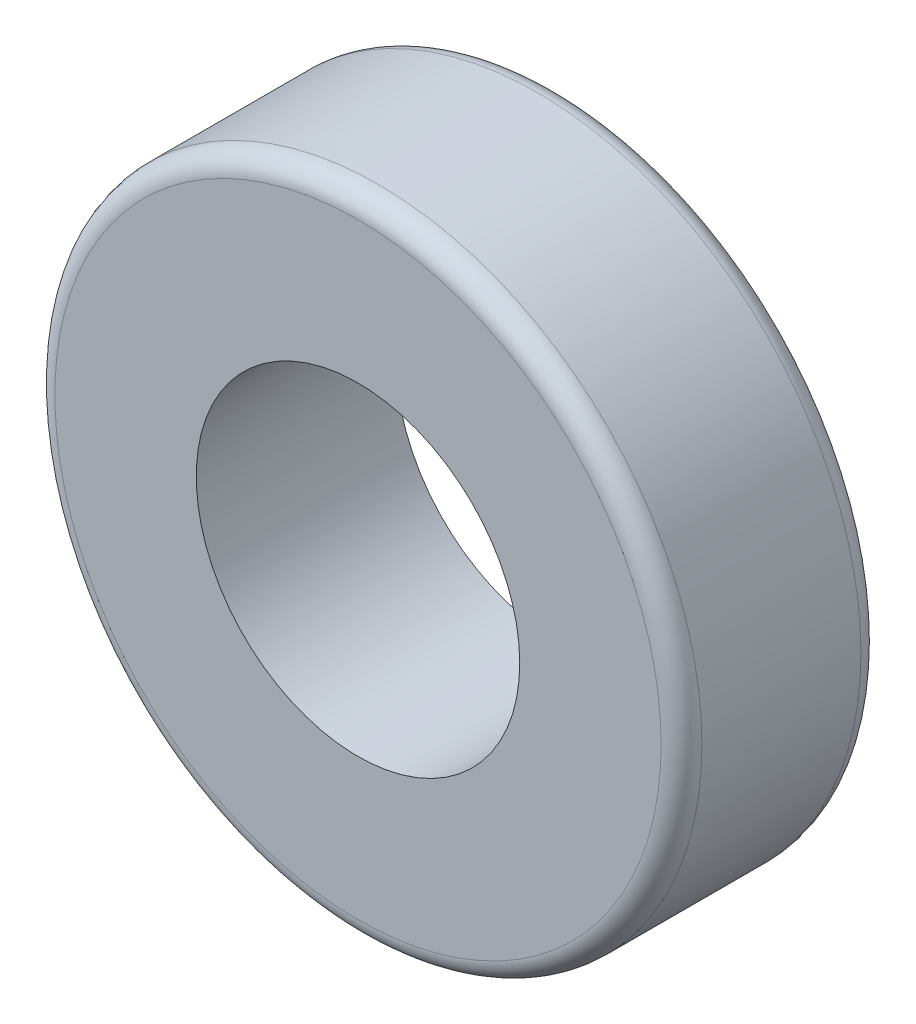
SolidWorks part; units mm, degrees
material "Plain Carbon Steel"
ref_plane "Front Plane" through (0, 0, 0) normal (0, 0, 1) x (1, 0, 0)
ref_plane "Top Plane" through (0, 0, 0) normal (0, 1, 0) x (1, 0, 0)
ref_plane "Right Plane" through (0, 0, 0) normal (1, 0, 0) x (0, 0, -1)
sketch "Sketch1" plane through (0, 0, 0) normal (0, 0, 1) x (1, 0, 0)
  circle A0 centre (0, 0) radius 7.9375
  circle A1 centre (0, 0) radius 3.9688
  dimension "D1" = 15.875
  dimension "D2" = 7.9375
extrude "Boss-Extrude1" add sketch "Sketch1" along normal blind 4.9022
fillet "Fillet1" radius 0.5 2 edges at (7.9375, 0, 0) (7.9375, 0, 4.9022)
